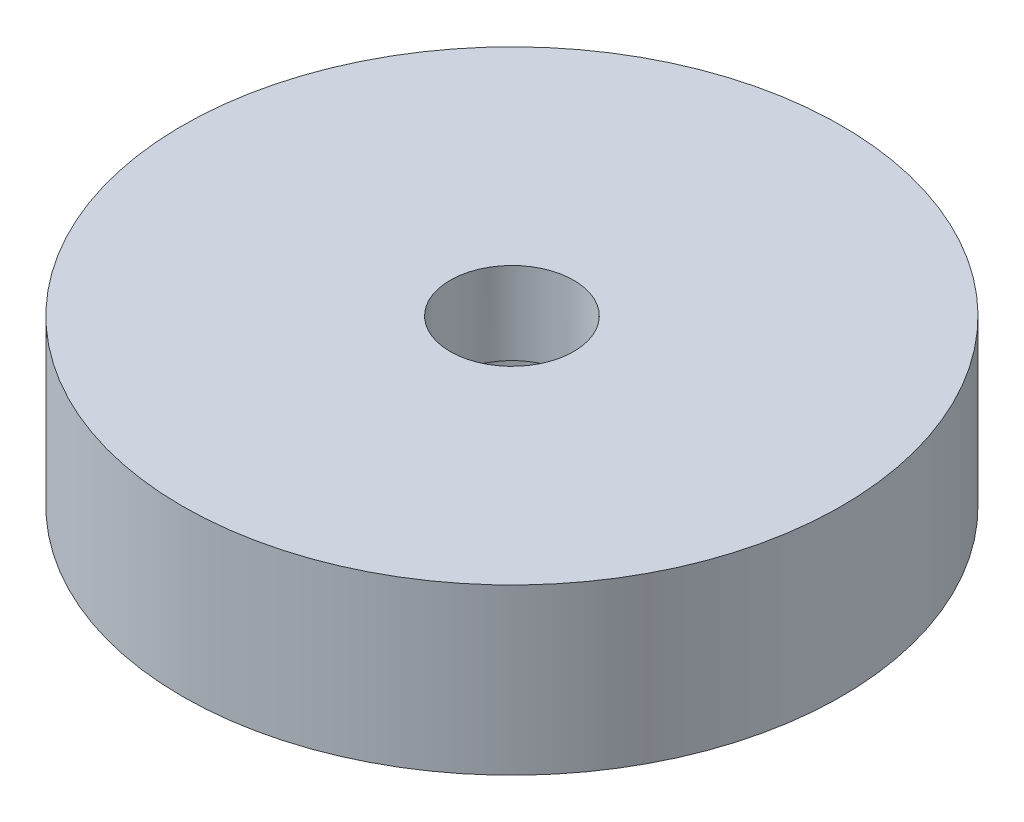
SolidWorks part; units mm, degrees
material "PVC Rigid"
ref_plane "Front Plane" through (0, 0, 0) normal (0, 0, 1) x (1, 0, 0)
ref_plane "Top Plane" through (0, 0, 0) normal (0, 1, 0) x (1, 0, 0)
ref_plane "Right Plane" through (0, 0, 0) normal (1, 0, 0) x (0, 0, -1)
sketch "Sketch1" plane through (0, 0, 0) normal (0, 1, 0) x (1, 0, 0)
  circle A0 centre (0, 0) radius 25.4
  dimension "D1" = 50.8
extrude "Boss-Extrude1" add sketch "Sketch1" along normal blind 12.7
sketch "Sketch2" plane through (0, 12.7, 0) normal (0, 1, 0) x (1, 0, 0)
  circle A0 centre (0, 0) radius 4.7625
  dimension "D1" = 9.525
extrude "Cut-Extrude1" cut sketch "Sketch2" against normal blind 12.7
sketch "Sketch4" plane through (0, 0, 0) normal (0, -1, 0) x (-1, 0, 0)
  circle A0 centre (0, 0) radius 9.525
  dimension "D1" = 19.05
extrude "Cut-Extrude3" cut sketch "Sketch4" against normal blind 6.35
